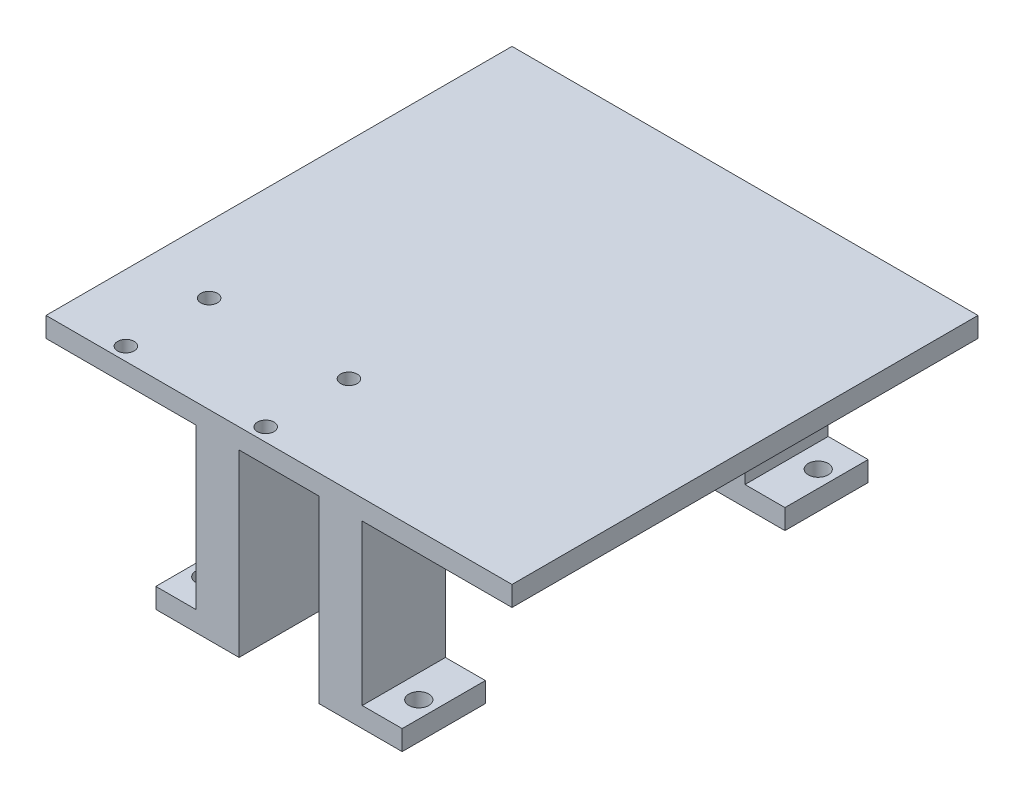
SolidWorks part; units mm, degrees
ref_plane "前基準面" through (0, 0, 0) normal (0, 0, 1) x (1, 0, 0)
ref_plane "上基準面" through (0, 0, 0) normal (0, 1, 0) x (1, 0, 0)
ref_plane "右基準面" through (0, 0, 0) normal (1, 0, 0) x (0, 0, -1)
sketch "草圖1" plane through (0, 0, 0) normal (0, 0, 1) x (1, 0, 0)
  line L0 (-194.1055, 0) -> (9511.1671, 0) construction
  line L1 (0, -194.1055) -> (0, 9511.1671) construction
  line L2 (-18.5, 0) -> (-18.5, 3)
  line L3 (-18.5, 3) -> (-12.5, 3)
  line L4 (-12.5, 3) -> (-12.5, 27)
  line L5 (-12.5, 27) -> (-35, 27)
  line L6 (-35, 27) -> (-35, 30)
  line L7 (-35, 30) -> (35, 30)
  line L8 (35, 30) -> (35, 27)
  line L9 (35, 27) -> (12.5, 27)
  line L10 (12.5, 27) -> (12.5, 3)
  line L11 (12.5, 3) -> (18.5, 3)
  line L12 (18.5, 3) -> (18.5, 0)
  line L13 (18.5, 0) -> (-18.5, 0)
  dimension "D1" = 37
  dimension "D2" = 30
  dimension "D3" = 3
  dimension "D4" = 3
  dimension "D5" = 70
  dimension "D6" = 25
extrude "填料-伸長1" add sketch "草圖1" along normal mid plane 70
sketch "草圖2" plane through (0, 0, 0) normal (1, 0, 0) x (0, 0, -1)
  line L0 (0, -1000) -> (0, 49000) construction
  line L1 (-35, 27) -> (35, 27) construction
  line L2 (-22.5, 27) -> (22.5, 27)
  line L3 (-22.5, 27) -> (-22.5, 0)
  line L4 (-22.5, 0) -> (22.5, 0)
  line L5 (22.5, 27) -> (22.5, 0)
  line L6 (-35, 0) -> (35, 0) construction
  dimension "D1" = 45
extrude "除料-伸長1" cut sketch "草圖2" against normal mid plane 70
sketch "草圖3" plane through (0, 0, 0) normal (0, 0, 1) x (1, 0, 0)
  line L0 (0, -1000) -> (0, 49000) construction
  line L1 (-1034.3623, 27) -> (48965.6377, 27) construction
  line L3 (-18.5, 0) -> (18.5, 0) construction
  line L4 (-6, 27) -> (6, 27)
  line L5 (-6, 27) -> (-6, 0)
  line L6 (-6, 0) -> (6, 0)
  line L7 (6, 27) -> (6, 0)
  dimension "D1" = 12
extrude "除料-伸長2" cut sketch "草圖3" against normal mid plane 80
sketch "草圖4" plane through (0, 0, 0) normal (0, 1, 0) x (1, 0, 0)
  line L0 (0, -1000) -> (0, 49000) construction
  line L1 (-16, -1000.5605) -> (-16, 48999.4395) construction
  line L2 (16, -998.3184) -> (16, 49001.6816) construction
  line L3 (-1012.7054, -30) -> (48987.2946, -30) construction
  line L4 (-1012.7054, 30) -> (48987.2946, 30) construction
  circle A0 centre (-16, -30) radius 1.5
  circle A1 centre (16, -30) radius 1.5
  circle A2 centre (16, 30) radius 1.5
  circle A3 centre (-16, 30) radius 1.5
  point P19 (0, 0)
  dimension "D5" = 3
  dimension "D2" = 16
  dimension "D3" = 60
  dimension "D4" = 30
extrude "除料-伸長3" cut sketch "草圖4" along normal blind 19
sketch "草圖5" plane through (0, 30, 0) normal (0, 1, 0) x (1, 0, 0)
  line L0 (-4, -1016.6487) -> (-4, 48983.3513) construction
  line L1 (-25, -1007.7841) -> (-25, 48992.2159) construction
  line L2 (-1004.144, -20.5) -> (48995.856, -20.5) construction
  line L3 (-1004.144, -33) -> (48995.856, -33) construction
  line L5 (35, -35) -> (-35, -35) construction
  line L6 (-35, -35) -> (-35, 35) construction
  circle A0 centre (-4, -20.5) radius 1.25
  circle A1 centre (-4, -33) radius 1.25
  circle A2 centre (-25, -33) radius 1.25
  circle A3 centre (-25, -20.5) radius 1.25
  dimension "D1" = 2.5
  dimension "D2" = 21
  dimension "D3" = 12.5
  dimension "D4" = 10
  dimension "D5" = 2
extrude "除料-伸長4" cut sketch "草圖5" against normal mid plane 10
